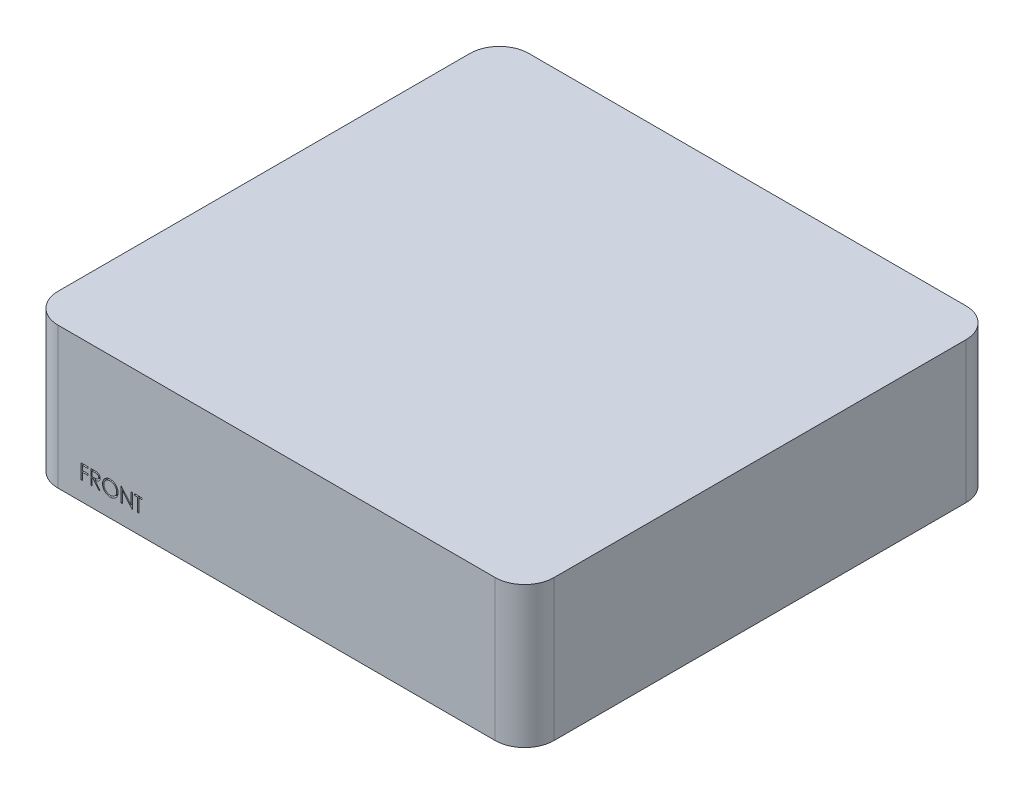
SolidWorks part; units mm, degrees
other "Markup1"
sketch "Sketch2" plane through (118, 33.6, -112) normal (0.1654, 0.289, -0.9429) x (-0.9648, -0.1507, -0.2155)
ref_plane "Front Plane" through (0, 0, 0) normal (0, 0, 1) x (1, 0, 0)
ref_plane "Top Plane" through (0, 0, 0) normal (0, 1, 0) x (1, 0, 0)
ref_plane "Right Plane" through (0, 0, 0) normal (1, 0, 0) x (0, 0, -1)
sketch "Sketch1" plane through (0, 0, 0) normal (0, 1, 0) x (1, 0, 0)
  line L1 (118, 0) -> (0, 0)
  line L2 (118, 0) -> (118, 112)
  line L3 (118, 112) -> (0, 112)
  line L4 (0, 0) -> (0, 112)
  dimension "D1" = 112
  dimension "D2" = 118
extrude "Boss-Extrude1" add sketch "Sketch1" along normal blind 33.6 contours L4 L3 L2 L1
fillet "Fillet2" radius 7 4 edges at (0, 16.8, -112) (118, 16.8, -112) (118, 16.8, 0) (0, 16.8, 0)
sketch "Sketch4" plane through (0, 0, 0) normal (0, 0, 1) x (1, 0, 0)
  text T0 "FRONT"
  point P1 (0, 0)
extrude "Cut-Extrude1" cut sketch "Sketch4" against normal blind 1
